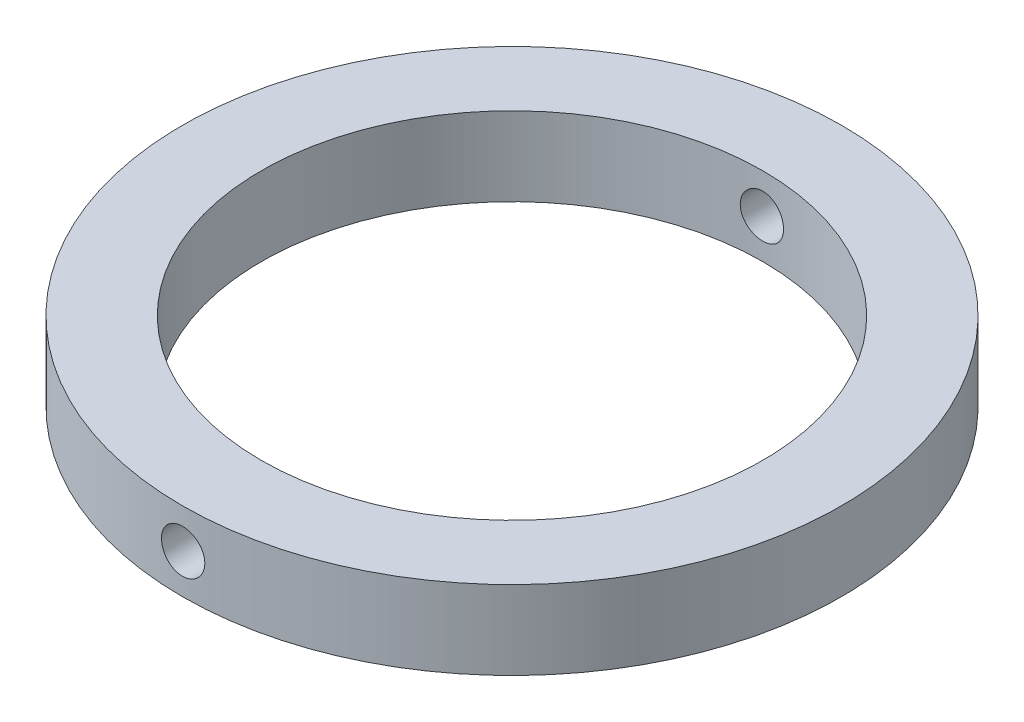
SolidWorks part; units mm, degrees
ref_plane "Front Plane" through (0, 0, 0) normal (0, 0, 1) x (1, 0, 0)
ref_plane "Top Plane" through (0, 0, 0) normal (0, 1, 0) x (1, 0, 0)
ref_plane "Right Plane" through (0, 0, 0) normal (1, 0, 0) x (0, 0, -1)
sketch "Sketch1" plane through (0, 0, 0) normal (0, 1, 0) x (1, 0, 0)
  circle A0 centre (0, 0) radius 41.85
  circle A1 centre (0, 0) radius 31.85
  dimension "D1" = 83.7
  dimension "D2" = 63.7
extrude "Boss-Extrude1" add sketch "Sketch1" along normal blind 10
sketch "Sketch5" plane through (0, 0, 0) normal (0, 0, 1) x (1, 0, 0)
  line L0 (41.85, 10) -> (-41.85, 10) construction
  circle A0 centre (0, 5) radius 2.75
  dimension "D1" = 5.5
  dimension "D2" = 5
extrude "Cut-Extrude1" cut sketch "Sketch5" along normal through all both and the other way through all
